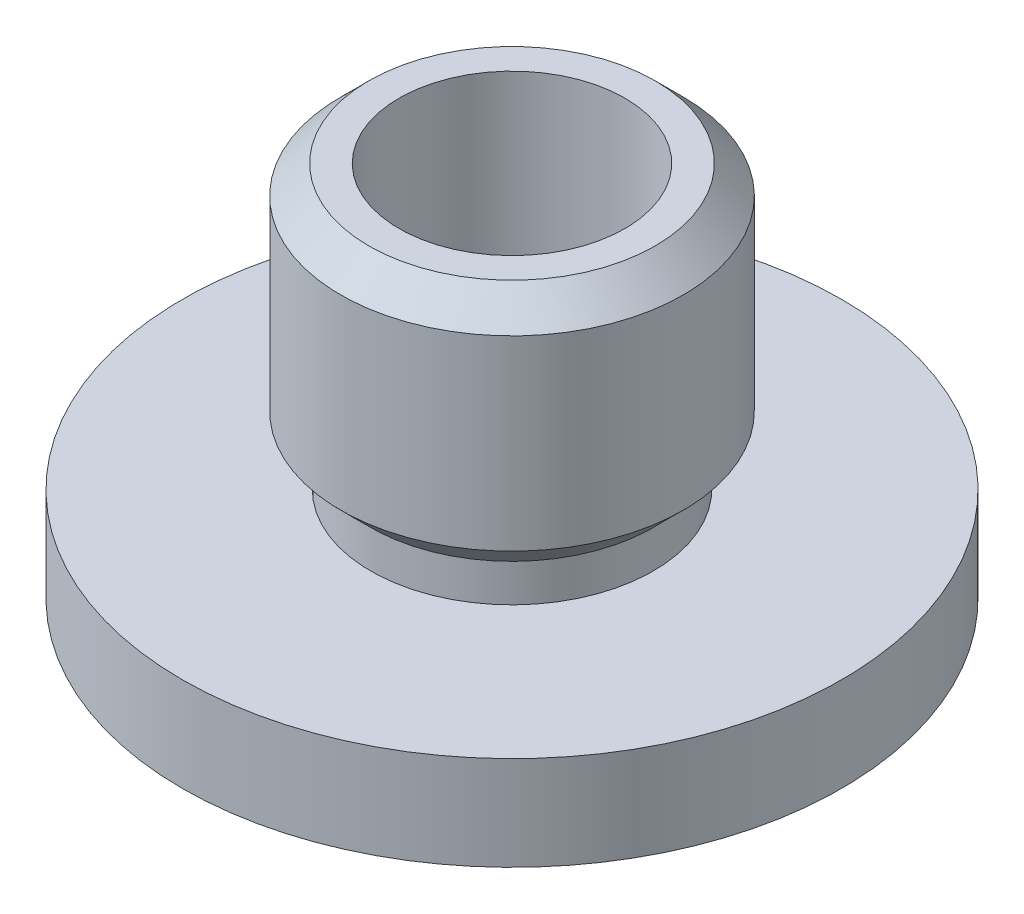
SolidWorks part; units mm, degrees
ref_plane "Front Plane" through (0, 0, 0) normal (0, 0, 1) x (1, 0, 0)
ref_plane "Top Plane" through (0, 0, 0) normal (0, 1, 0) x (1, 0, 0)
ref_plane "Right Plane" through (0, 0, 0) normal (1, 0, 0) x (0, 0, -1)
sketch "Sketch1" plane through (0, 0, 0) normal (0, 0, 1) x (1, 0, 0)
  line L0 (0, -65.9597) -> (0, 0) construction
  line L2 (6, 0) -> (7.6, 0)
  line L3 (7.6, 0) -> (9.1, -1.5)
  line L4 (9.1, -1.5) -> (9.1, -11.4)
  line L5 (9.1, -11.4) -> (7.5, -13)
  line L6 (7.5, -13) -> (7.5, -15)
  line L7 (7.5, -15) -> (17.5, -15)
  line L8 (17.5, -15) -> (17.5, -20)
  line L9 (17.5, -20) -> (6, -20)
  line L10 (6, 0) -> (6, -20)
  point P10 (0, -65.9597)
  point P12 (0, 0)
  dimension "D1" = 18.2
  dimension "D2" = 45
  dimension "D3" = 15
  dimension "D4" = 2
  dimension "D5" = 45
  dimension "D6" = 1.5
  dimension "D7" = 15
  dimension "D8" = 5
  dimension "D9" = 35
  dimension "D10" = 12
revolve "Revolve1" add sketch "Sketch1" angle 360 about L0
